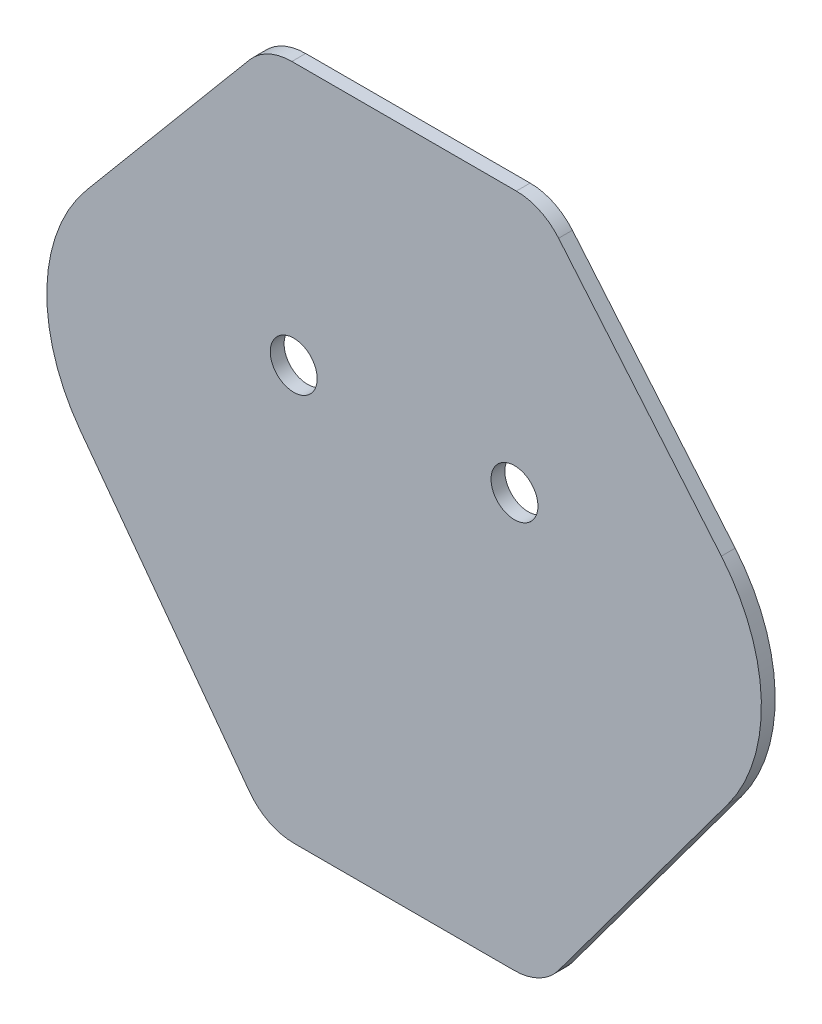
SolidWorks part; units mm, degrees
ref_plane "Front Plane" through (0, 0, 0) normal (0, 0, 1) x (1, 0, 0)
ref_plane "Top Plane" through (0, 0, 0) normal (0, 1, 0) x (1, 0, 0)
ref_plane "Right Plane" through (0, 0, 0) normal (1, 0, 0) x (0, 0, -1)
sketch "Sketch1" plane through (0, 0, 0) normal (0, 0, 1) x (1, 0, 0)
  line L0 (-63.5, 155.575) -> (-185.951, 9.6435)
  line L1 (63.5, -155.575) -> (-63.5, -155.575)
  line L3 (63.5, 155.575) -> (-63.5, 155.575)
  line L7 (-185.951, 9.6435) -> (-63.5, -155.575)
  line L8 (63.5, 155.575) -> (185.951, 9.6435)
  line L9 (185.951, 9.6435) -> (63.5, -155.575)
  circle A0 centre (-50.8, 34.925) radius 10.795
  circle A1 centre (50.8, 34.925) radius 10.795
  point P0 (0, 0)
  dimension "D6" = 21.59
  dimension "D7" = 21.59
  dimension "D8" = 101.6
  dimension "D9" = 135.151
  dimension "D10" = 25.2815
  dimension "D11" = 25.2815
  dimension "D1" = 311.15
  dimension "D2" = 127
  dimension "D3" = 190.5
  dimension "D4" = 127
  dimension "D5" = 190.5
  dimension "D12" = 130
  dimension "D13" = 103.456
  dimension "D14" = 126.544
extrude "Boss-Extrude1" add sketch "Sketch1" along normal mid plane 6.35
fillet "Fillet1" radius 25.4 4 edges at (63.5, -155.575, 0) (-63.5, -155.575, 0) (63.5, 155.575, 0) (-63.5, 155.575, 0)
fillet "Fillet2" radius 78.74 2 edges at (185.951, 9.6435, 0) (-185.951, 9.6435, 0)
